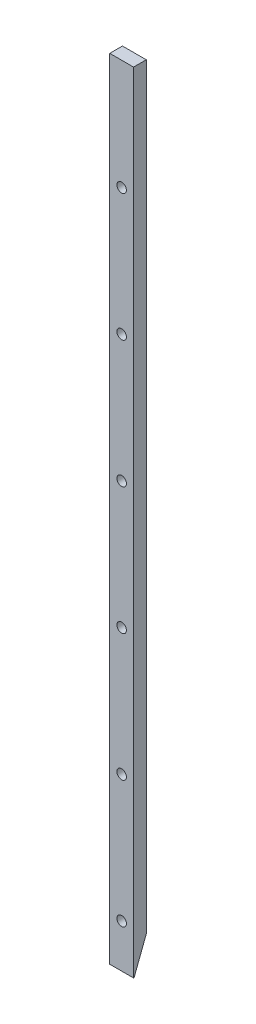
SolidWorks part; units mm, degrees
material "Brass"
ref_plane "Front Plane" through (0, 0, 0) normal (0, 0, 1) x (1, 0, 0)
ref_plane "Top Plane" through (0, 0, 0) normal (0, 1, 0) x (1, 0, 0)
ref_plane "Right Plane" through (0, 0, 0) normal (1, 0, 0) x (0, 0, -1)
sketch "Sketch1" plane through (0, 0, 0) normal (0, 0, 1) x (1, 0, 0)
  line L1 (-7.5, -248.41) -> (7.5, -248.41)
  line L2 (-7.5, -248.41) -> (-7.5, 248.41)
  line L3 (-7.5, 248.41) -> (7.5, 248.41)
  line L4 (7.5, -248.41) -> (7.5, 248.41)
  line L5 (-7.5, -248.41) -> (7.5, 248.41) construction
  line L6 (-7.5, 248.41) -> (7.5, -248.41) construction
  point P0 (0, 0)
  dimension "D1" = 496.82
  dimension "D2" = 15
extrude "Boss-Extrude1" add sketch "Sketch1" along normal mid plane 8
sketch "Sketch2" plane through (0, 0, 4) normal (0, 0, 1) x (1, 0, 0)
  line L0 (7.5, 248.41) -> (-7.5, 248.41) construction
  line L1 (-7.5, 248.41) -> (-7.5, -248.41) construction
  circle A0 centre (0, 178.9523) radius 3
  dimension "D1" = 6
  dimension "D3" = 7.5
  dimension "D2" = 69.4577
extrude "Cut-Extrude1" cut sketch "Sketch2" against normal blind 8
chamfer "Chamfer1" distance 20 angle 21 1 edges at (0, -248.41, -4)
pattern_linear "LPattern1" count 6 spacing 80 along (0, -1, 0) of "Cut-Extrude1"
chamfer "Chamfer3" distance 3 angle 45 6 edges at (3, 178.9523, -4) (3, 98.9523, -4) (3, 18.9523, -4) (3, -61.0477, -4) (3, -141.0477, -4) (3, -221.0477, -4)
